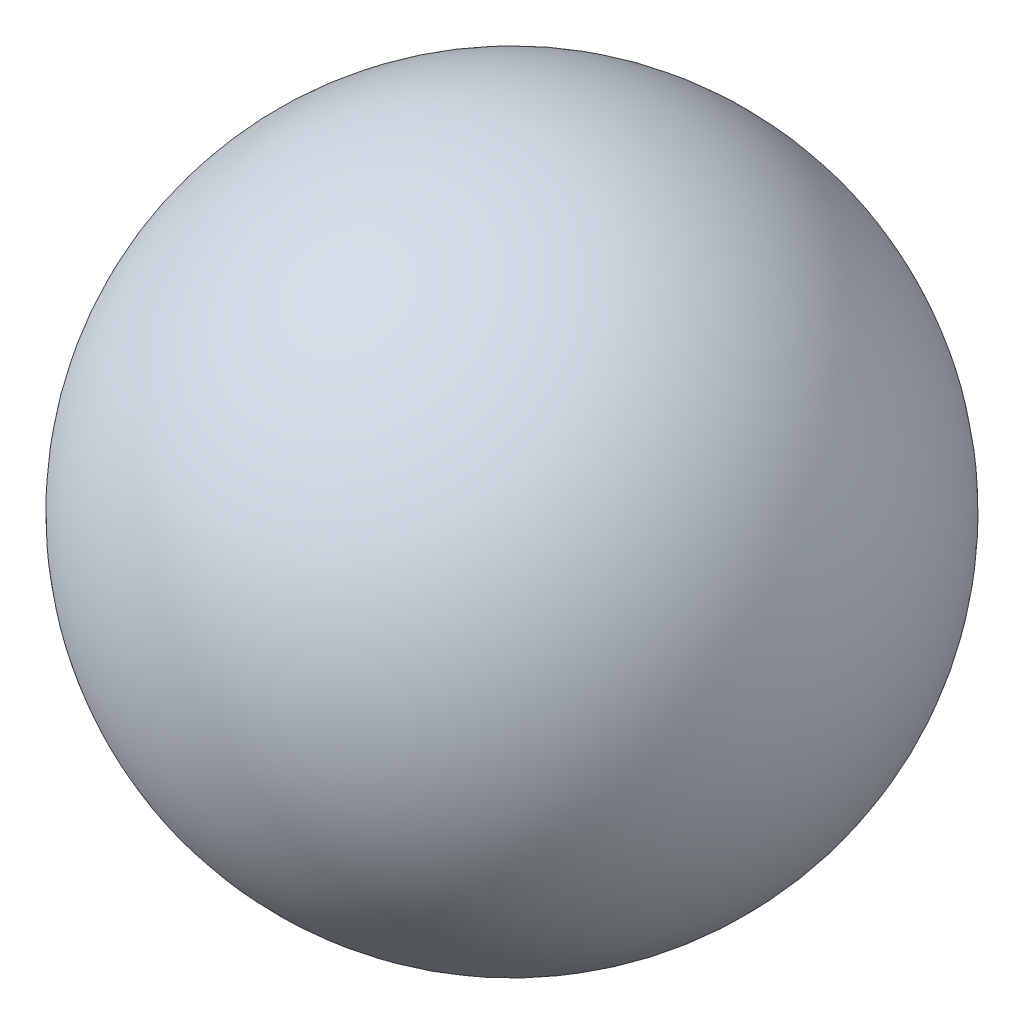
SolidWorks part; units mm, degrees
ref_plane "Front Plane" through (0, 0, 0) normal (0, 0, 1) x (1, 0, 0)
ref_plane "Top Plane" through (0, 0, 0) normal (0, 1, 0) x (1, 0, 0)
ref_plane "Right Plane" through (0, 0, 0) normal (1, 0, 0) x (0, 0, -1)
sketch "Sketch1" plane through (0, 0, 0) normal (0, 1, 0) x (1, 0, 0)
  line L0 (0, 4) -> (0, -4)
  arc A0 (0, -4) -> (0, 4) centre (0, 0) ccw
  point P3 (0, 0)
  dimension "D1" = 8
revolve "Revolve1" add sketch "Sketch1" angle 360 about L0
